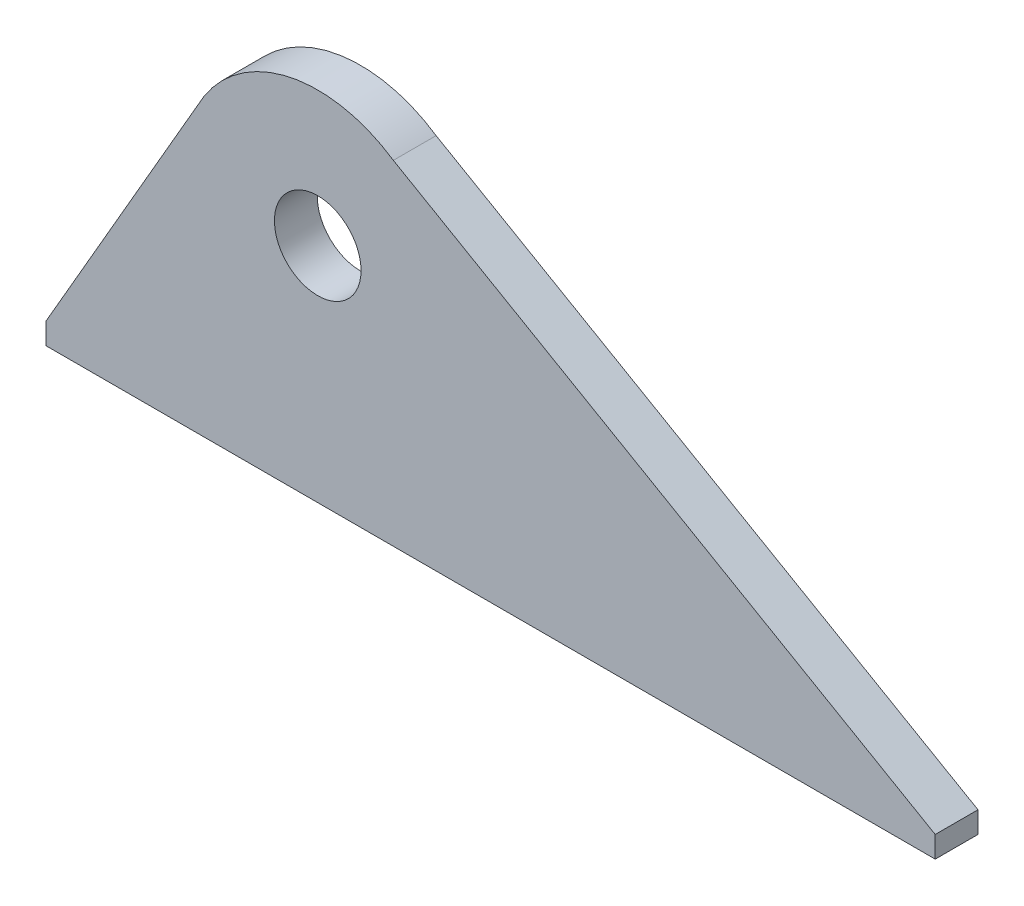
SolidWorks part; units mm, degrees
ref_plane "Plan de face" through (0, 0, 0) normal (0, 0, 1) x (1, 0, 0)
ref_plane "Plan de dessus" through (0, 0, 0) normal (0, 1, 0) x (1, 0, 0)
ref_plane "Plan de droite" through (0, 0, 0) normal (1, 0, 0) x (0, 0, -1)
sketch "Esquisse1" plane through (0, 0, 0) normal (0, 0, 1) x (1, 0, 0)
  line L0 (0, 0) -> (207.8786, 0)
  line L1 (207.8786, 0) -> (207.8786, 5)
  line L2 (207.8786, 5) -> (86.635, 75) construction
  line L3 (86.635, 75) -> (40.4145, 75) construction
  line L4 (40.4145, 75) -> (0, 5) construction
  line L5 (0, 5) -> (0, 0)
  line L6 (0, 5) -> (207.8786, 5) construction
  line L7 (63.5248, 75) -> (63.5248, 5) construction
  line L8 (207.8786, 5) -> (51.9696, 95.0141) construction
  line L9 (0, 5) -> (51.9696, 95.0141) construction
  line L10 (207.8786, 5) -> (81.2013, 78.1372)
  line L11 (36.9325, 68.969) -> (0, 5)
  arc A0 (36.9325, 68.969) -> (81.2013, 78.1372) centre (63.5248, 52.0281) cw
  circle A1 centre (63.5248, 52.0281) radius 10.125
  circle A2 centre (63.5248, 52.0281) radius 31.5 construction
  dimension "D6" = 63
  dimension "D7" = 0.03
  dimension "D8" = 20.25
  dimension "D5" = 70
  dimension "D1" = 5
  dimension "D2" = 207.8786
  dimension "D3" = 60
  dimension "D4" = 30
extrude "Boss.-Extru.1" add sketch "Esquisse1" along normal blind 10
